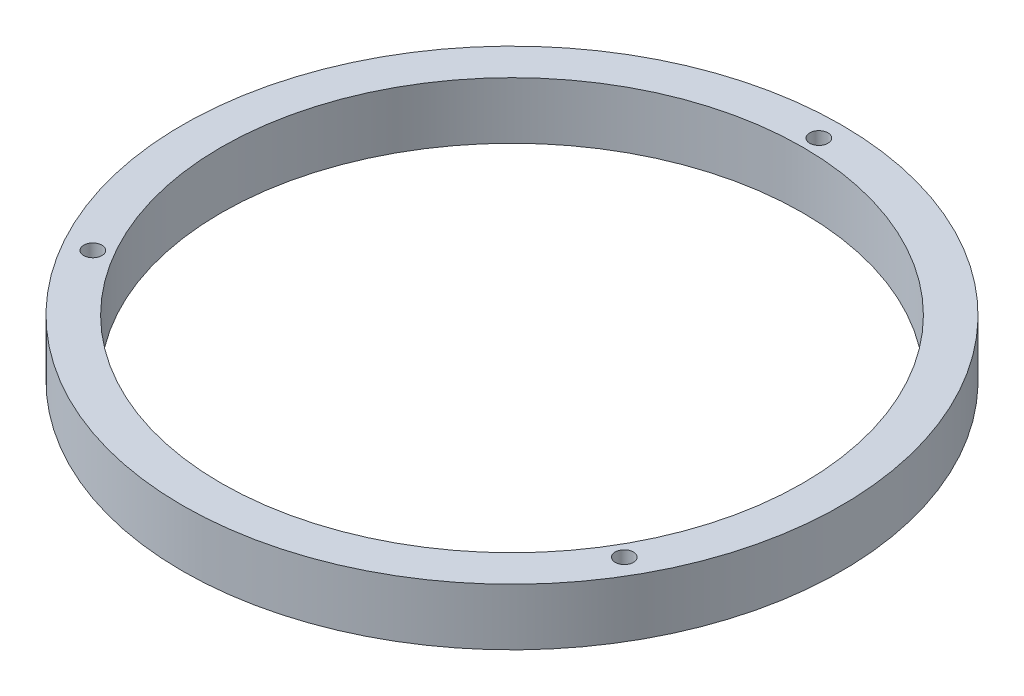
SolidWorks part; units mm, degrees
ref_plane "Front" through (0, 0, 0) normal (0, 0, 1) x (1, 0, 0)
ref_plane "Top" through (0, 0, 0) normal (0, 1, 0) x (1, 0, 0)
ref_plane "Right" through (0, 0, 0) normal (1, 0, 0) x (0, 0, -1)
sketch "Sketch1" plane through (0, 0, 0) normal (0, 1, 0) x (1, 0, 0)
  line L0 (0, -55) -> (0, 55) construction
  circle A0 centre (0, 0) radius 64
  circle A1 centre (0, 0) radius 72.5
  circle A2 centre (0, 67.5) radius 2
  circle A3 centre (58.4567, -33.75) radius 2
  circle A4 centre (-58.4567, -33.75) radius 2
  point P14 (0, 0)
  dimension "D1" = 128
  dimension "D2" = 145
  dimension "D3" = 4
  dimension "D4" = 67.5
  dimension "D5" = 3
extrude "Boss-Extrude1" add sketch "Sketch1" along normal blind 12.5 contours A1 A2 A0
